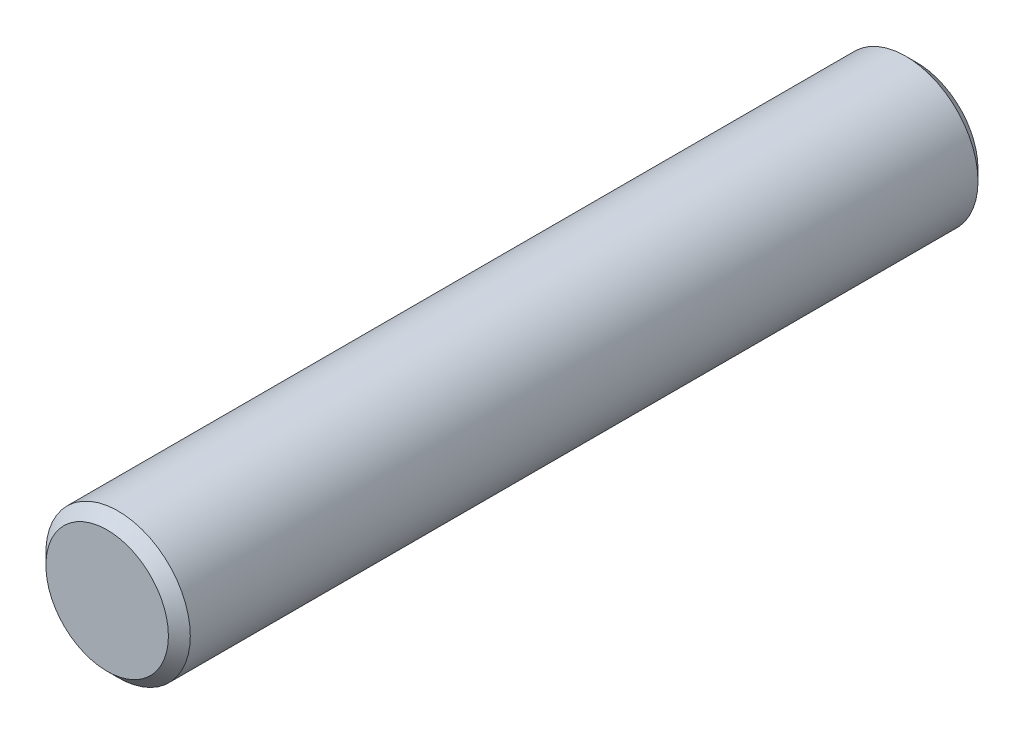
SolidWorks part; units mm, degrees
ref_plane "Front Plane" through (0, 0, 0) normal (0, 0, 1) x (1, 0, 0)
ref_plane "Top Plane" through (0, 0, 0) normal (0, 1, 0) x (1, 0, 0)
ref_plane "Right Plane" through (0, 0, 0) normal (1, 0, 0) x (0, 0, -1)
sketch "Sketch1" plane through (0, 0, 0) normal (0, 0, 1) x (1, 0, 0)
  circle A0 centre (0, 0) radius 3.3
  dimension "D1" = 6.6
extrude "Boss-Extrude1" add sketch "Sketch1" along normal blind 37
chamfer "Chamfer1" distance 0.5 angle 45 2 edges at (3.3, 0, 0) (3.3, 0, 37)
